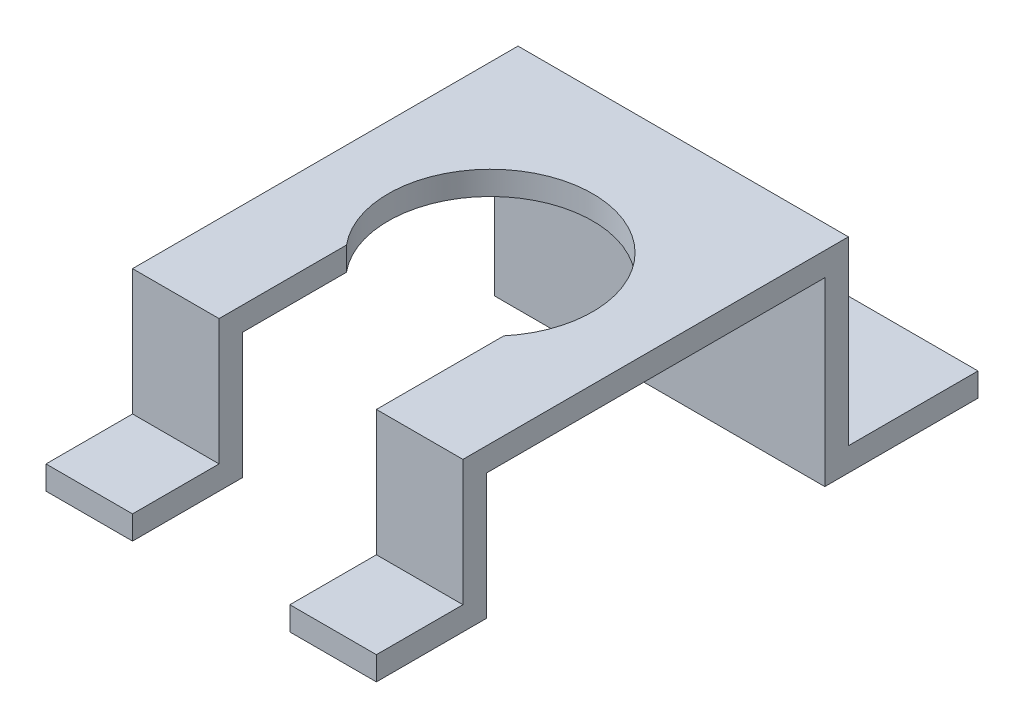
SolidWorks part; units mm, degrees
ref_plane "Front Plane" through (0, 0, 0) normal (0, 0, 1) x (1, 0, 0)
ref_plane "Top Plane" through (0, 0, 0) normal (0, 1, 0) x (1, 0, 0)
ref_plane "Right Plane" through (0, 0, 0) normal (1, 0, 0) x (0, 0, -1)
sketch "Sketch2" plane through (0, 0, 0) normal (1, 0, 0) x (0, 0, -1)
  line L0 (74.5887, 0) -> (94.0628, 0)
  line L1 (94.0628, 0) -> (94.0628, 3)
  line L2 (94.0628, 3) -> (77.5887, 3)
  line L3 (77.5887, 3) -> (77.5887, 26)
  line L4 (77.5887, 26) -> (28.5887, 26)
  line L5 (28.5887, 26) -> (28.5887, 10)
  line L6 (28.5887, 10) -> (17.5887, 10)
  line L7 (17.5887, 10) -> (17.5887, 7)
  line L8 (17.5887, 7) -> (31.5887, 7)
  line L9 (31.5887, 7) -> (31.5887, 23)
  line L10 (31.5887, 23) -> (74.5887, 23)
  line L11 (74.5887, 23) -> (74.5887, 0)
  point P12 (24.5887, 7)
  dimension "D1" = 43
  dimension "D2" = 23
  dimension "D3" = 16
  dimension "D4" = 3
  dimension "D5" = 3
  dimension "D6" = 3
  dimension "D7" = 3
  dimension "D8" = 3
  dimension "D9" = 14
extrude "Boss-Extrude1" add sketch "Sketch2" along normal blind 42 contours L4 L5 L6 L7 L8 L9 L10 L11 L0 L1 L2 L3
sketch "Sketch3" plane through (0, 26, 0) normal (0, 1, 0) x (1, 0, 0)
  line L0 (0, 77.5887) -> (42, 28.5887) construction
  line L1 (42, 28.5887) -> (42, 77.5887) construction
  line L2 (42, 77.5887) -> (0, 28.5887) construction
  line L3 (11, 17.5887) -> (11, 44.7821)
  line L4 (42, 17.5887) -> (0, 17.5887) construction
  line L5 (0, 28.5887) -> (0, 17.5887) construction
  line L6 (21, 53.0887) -> (21, 28.5887) construction
  line L7 (42, 28.5887) -> (0, 28.5887) construction
  line L8 (31, 17.5887) -> (31, 44.7821)
  line L9 (11, 17.5887) -> (31, 17.5887)
  arc A0 (31, 44.7821) -> (11, 44.7821) centre (21, 53.0887) ccw
  dimension "D1" = 26
  dimension "D2" = 11
extrude "Cut-Extrude1" cut sketch "Sketch3" against normal through all
